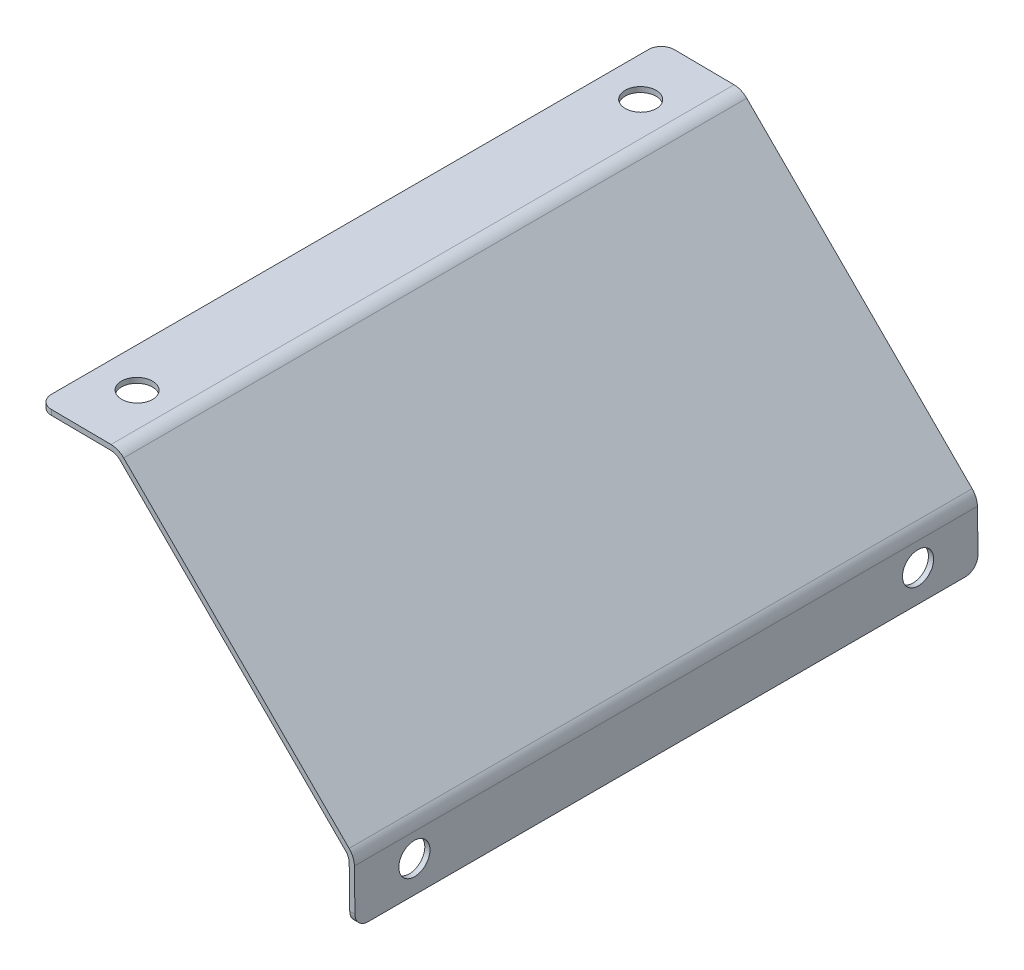
SolidWorks part; units mm, degrees
ref_plane "Piano frontale" through (0, 0, 0) normal (0, 0, 1) x (1, 0, 0)
ref_plane "Piano superiore" through (0, 0, 0) normal (0, 1, 0) x (1, 0, 0)
ref_plane "Piano destro" through (0, 0, 0) normal (1, 0, 0) x (0, 0, -1)
sketch "Schizzo1" plane through (0, 0, 0) normal (0, 0, 1) x (1, 0, 0)
  line L0 (0, 120) -> (30, 119.7082)
  line L1 (30, 119.7082) -> (119.7082, 30)
  line L2 (119.7082, 30) -> (120, 7)
  point P4 (-180.1504, -9.2365)
extrude "Estrusione-Sottile1" add sketch "Schizzo1" along normal up to surface (120 mm away) and the other way up to surface (120 mm away) thin thin type one direction reverse wall 2
fillet "Raccordo1" radius 5 2 edges at (120.9999, 7.0127, -120) (120.9999, 7.0127, 120)
fillet "Raccordo2" radius 5 2 edges at (0.0097, 121, 120) (0.0097, 121, -120)
sketch "Schizzo7" plane through (1.1865, 121.9886, 0) normal (0.0097, 1, 0) x (1, -0.0097, 0)
  circle A0 centre (13.8322, -97) radius 6
  circle A1 centre (13.8322, 97) radius 6
  ellipse E0 centre (13.8322, -97) end of major axis (13.8322, -93.5) minor radius 3.4998 construction
  ellipse E1 centre (13.8322, 97) end of major axis (13.8322, 93.5) minor radius 3.4998 construction
  dimension "D1" = 12
sketch "Schizzo8" plane through (122.0693, 1.5487, 0) normal (0.9999, 0.0127, 0) x (0, 0, -1)
  circle A0 centre (-97, 17.4762) radius 6
  circle A1 centre (97, 17.4762) radius 6
  ellipse E0 centre (-97, 17.4762) end of major axis (-100.5, 17.4762) minor radius 3.4997 construction
  ellipse E1 centre (97, 17.4762) end of major axis (100.5, 17.4762) minor radius 3.4997 construction
  dimension "D1" = 12
extrude "Taglio-Estrusione1" cut sketch "Schizzo8" against normal through all
extrude "Taglio-Estrusione2" cut sketch "Schizzo7" against normal through all
